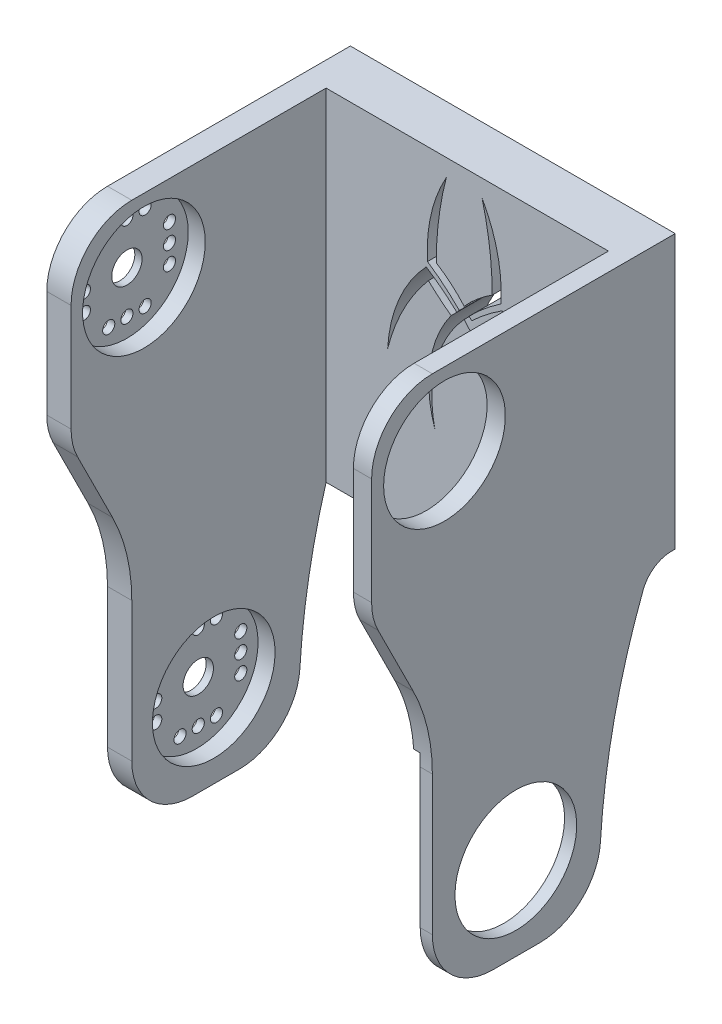
SolidWorks part; units mm, degrees
ref_plane "Front Plane" through (0, 0, 0) normal (0, 0, 1) x (1, 0, 0)
ref_plane "Top Plane" through (0, 0, 0) normal (0, 1, 0) x (1, 0, 0)
ref_plane "Right Plane" through (0, 0, 0) normal (1, 0, 0) x (0, 0, -1)
sketch "Sketch1" plane through (0, 0, 0) normal (0, 1, 0) x (1, 0, 0)
  line L0 (-23.25, 0) -> (-23.25, 42)
  line L1 (-23.25, 42) -> (23.25, 42)
  line L2 (23.25, 42) -> (23.25, 0)
  line L3 (23.25, 0) -> (26.25, 0)
  line L4 (26.25, 0) -> (26.25, 50)
  line L5 (26.25, 50) -> (-27.25, 50)
  line L6 (-27.25, 50) -> (-27.25, 0)
  line L7 (-27.25, 0) -> (-23.25, 0)
  dimension "D1" = 4
  dimension "D2" = 3
  dimension "D3" = 46.5
  dimension "D4" = 23.25
  dimension "D5" = 8
  dimension "D6" = 50
  dimension "D7" = 50
extrude "Boss-Extrude1" add sketch "Sketch1" along normal blind 90
sketch "Sketch2" plane through (-23.25, 0, 0) normal (1, 0, 0) x (0, 0, -1)
  line L0 (0, 90) -> (50, 90) construction
  line L1 (0, 90) -> (0, 0) construction
  circle A0 centre (12, 78) radius 10.1
  dimension "D3" = 20.2
  dimension "D1" = 12
  dimension "D2" = 12
extrude "Cut-Extrude1" cut sketch "Sketch2" against normal blind 2.8
sketch "Sketch3" plane through (-26.05, 0, 0) normal (1, 0, 0) x (0, 0, -1)
  line L0 (0, 90) -> (50, 90) construction
  line L2 (0, 90) -> (0, 0) construction
  circle A0 centre (12, 78) radius 2.5
  circle A1 centre (12, 85) radius 1
  circle A2 centre (9, 85) radius 1
  circle A3 centre (15, 85) radius 1
  circle A4 centre (19, 78) radius 1
  circle A5 centre (19, 81) radius 1
  circle A6 centre (19, 75) radius 1
  circle A7 centre (12, 71) radius 1
  circle A8 centre (15, 71) radius 1
  circle A9 centre (9, 71) radius 1
  circle A10 centre (5, 78) radius 1
  circle A11 centre (5, 75) radius 1
  circle A12 centre (5, 81) radius 1
  point P33 (12, 78)
  dimension "D1" = 5
  dimension "D2" = 2
  dimension "D7" = 2
  dimension "D8" = 2
  dimension "D3" = 5
  dimension "D4" = 12
  dimension "D5" = 7
  dimension "D6" = 12
  dimension "D9" = 3
  dimension "D10" = 3
  dimension "D11" = 4
extrude "Cut-Extrude2" cut sketch "Sketch3" against normal blind 2.8
sketch "Sketch4" plane through (-23.25, 0, 0) normal (1, 0, 0) x (0, 0, -1)
  line L0 (0, 0) -> (50, 0) construction
  line L1 (0, 90) -> (0, 0) construction
  circle A0 centre (23.5, 13.75) radius 10.1
  dimension "D1" = 20.2
  dimension "D2" = 13.75
  dimension "D3" = 23.5
extrude "Cut-Extrude3" cut sketch "Sketch4" against normal blind 2.8
sketch "Sketch5" plane through (-26.05, 0, 0) normal (1, 0, 0) x (0, 0, -1)
  line L0 (0, 90) -> (0, 0) construction
  line L1 (0, 0) -> (50, 0) construction
  circle A0 centre (23.75, 13.75) radius 2.5
  circle A1 centre (23.75, 20.75) radius 1
  circle A2 centre (20.75, 20.75) radius 1
  circle A3 centre (26.75, 20.75) radius 1
  circle A4 centre (30.75, 16.75) radius 1
  circle A5 centre (30.75, 13.75) radius 1
  circle A6 centre (30.75, 10.75) radius 1
  circle A7 centre (26.75, 6.75) radius 1
  circle A8 centre (23.75, 6.75) radius 1
  circle A9 centre (20.75, 6.75) radius 1
  circle A10 centre (16.75, 10.75) radius 1
  circle A11 centre (16.75, 13.75) radius 1
  circle A12 centre (16.75, 16.75) radius 1
  point P33 (23.75, 13.75)
  dimension "D1" = 5
  dimension "D2" = 2
  dimension "D6" = 2
  dimension "D7" = 2
  dimension "D3" = 7
  dimension "D4" = 23.75
  dimension "D5" = 13.75
  dimension "D8" = 3
  dimension "D9" = 3
  dimension "D10" = 4
extrude "Cut-Extrude4" cut sketch "Sketch5" against normal blind 2.8
sketch "Sketch6" plane through (23.25, 0, 0) normal (-1, 0, 0) x (0, 0, 1)
  circle A0 centre (-12, 78) radius 10.025
  circle A1 centre (-23.75, 13.75) radius 10.025
  dimension "D1" = 20.05
  dimension "D2" = 20.05
extrude "Cut-Extrude5" cut sketch "Sketch6" against normal blind 12.8
sketch "Sketch8" plane through (-27.25, 0, 0) normal (-1, 0, 0) x (0, 0, 1)
  line L0 (0, 60) -> (-6.8328, 46.3344)
  line L1 (0, 90) -> (0, 0) construction
  line L2 (-10, 32.918) -> (-10, 0)
  line L3 (-50, 0) -> (0, 0) construction
  line L4 (-10, 0) -> (0, 0)
  line L5 (0, 0) -> (0, 60)
  line L6 (-50, 45) -> (-49.384, 45)
  line L7 (-50, 90) -> (-50, 0) construction
  line L8 (-50, 45) -> (-50, 0)
  line L9 (-50, 0) -> (-37.5, 0)
  arc A0 (-6.8328, 46.3344) -> (-10, 32.918) centre (20, 32.918) ccw
  arc A1 (-44.7132, 41.7843) -> (-37.5, 0) centre (-147.4709, 2.5305) cw
  arc A2 (-49.384, 45) -> (-44.7132, 41.7843) centre (-49.384, 40) cw
  point P11 (-10, 40)
  point P21 (-46, 45)
  dimension "D4" = 30
  dimension "D6" = 110
  dimension "D9" = 5
  dimension "D1" = 10
  dimension "D2" = 60
  dimension "D3" = 20
  dimension "D5" = 12.5
  dimension "D7" = 4
  dimension "D8" = 45
extrude "Cut-Extrude7" cut sketch "Sketch8" against normal blind 62.8
fillet "Fillet1" radius 10 8 edges at (24.75, 60, 0) (-25.25, 60, 0) (-25.25, 90, 0) (24.75, 90, 0) (-25.25, 0, -37.5) (24.75, 0, -37.5) (24.75, 0, -10) (-25.25, 0, -10)
sketch "Sketch9" plane through (0, 0, 0) normal (0, 0, 1) x (1, 0, 0)
  line L1 (23.25, 0) -> (24.25, 0)
  line L2 (23.25, 0) -> (23.25, 35)
  line L3 (23.25, 35) -> (24.25, 35)
  line L4 (24.25, 0) -> (24.25, 35)
  dimension "D1" = 1
  dimension "D2" = 35
extrude "Cut-Extrude8" cut sketch "Sketch9" against normal blind 50
sketch "Sketch10" plane through (0, 0, -50) normal (0, 0, -1) x (-1, 0, 0)
  line L1 (-0.3142, 69.2468) -> (-0.7183, 68.7893)
  line L2 (1.3142, 69.2468) -> (1.7183, 68.7893)
  line L3 (0, 0) -> (28, 0)
  line L4 (-26.25, 9.3775) -> (-26.25, 0) construction
  line L5 (27.25, 0) -> (27.25, 9.3775) construction
  line L6 (27.25, 9.3775) -> (27.25, 41.7843) construction
  arc A0 (-2.4385, 87.1607) -> (-4.1062, 74.1485) centre (47.2089, 74.1848) ccw
  arc A1 (-4.1062, 74.1485) -> (0.5, 70.249) centre (-15.3664, 56.1774) cw
  arc A2 (-2.4385, 87.1607) -> (-5.5455, 73.6095) centre (19.0054, 75.1124) ccw
  arc A3 (-5.5518, 73.6137) -> (-0.3142, 69.2468) centre (-23.6018, 46.6405) cw
  arc A4 (-0.7183, 68.7893) -> (-5.7633, 72.7386) centre (-23.4701, 44.9216) ccw
  arc A5 (-1.6637, 67.841) -> (-5.3986, 70.9584) centre (22.7485, 100.8848) cw
  arc A6 (-5.7633, 72.7386) -> (-12.109, 57.8929) centre (11.4374, 56.6071) ccw
  arc A7 (-12.109, 57.8929) -> (-5.3986, 70.9584) centre (19.2304, 50.053) cw
  arc A8 (-1.6637, 67.841) -> (-4.327, 50.2876) centre (13.9797, 56.4888) ccw
  arc A9 (-4.327, 50.2876) -> (0.5, 68.3711) centre (15.2098, 54.7587) cw
  arc A10 (5.327, 50.2876) -> (0.5, 68.3711) centre (-14.2098, 54.7587) ccw
  arc A11 (2.6637, 67.841) -> (5.327, 50.2876) centre (-12.9797, 56.4888) cw
  arc A12 (6.7633, 72.7386) -> (13.109, 57.8929) centre (-10.4374, 56.6071) cw
  arc A13 (13.109, 57.8929) -> (6.3986, 70.9584) centre (-18.2304, 50.053) ccw
  arc A14 (2.6637, 67.841) -> (6.3986, 70.9584) centre (-21.7485, 100.8848) ccw
  arc A15 (1.7183, 68.7893) -> (6.7633, 72.7386) centre (24.4701, 44.9216) cw
  arc A16 (6.5518, 73.6137) -> (1.3142, 69.2468) centre (24.6018, 46.6405) ccw
  arc A17 (5.1062, 74.1485) -> (0.5, 70.249) centre (16.3664, 56.1774) ccw
  arc A18 (3.4385, 87.1607) -> (6.5455, 73.6095) centre (-18.0054, 75.1124) cw
  arc A19 (3.4385, 87.1607) -> (5.1062, 74.1485) centre (-46.2089, 74.1848) cw
  point P51 (20.6163, 3.5635)
  dimension "D1" = 28
  dimension "D2" = 26.25
  dimension "D3" = 27.25
  dimension "D4" = 26.75
extrude "Cut-Extrude10" cut sketch "Sketch10" against normal blind 10 contours A18 A19 A17 A1 A0 A2 A3 L1 A4 A6 A7 A5 A8 A9 A10 A11 A14 A13 A12 A15 L2 A16
